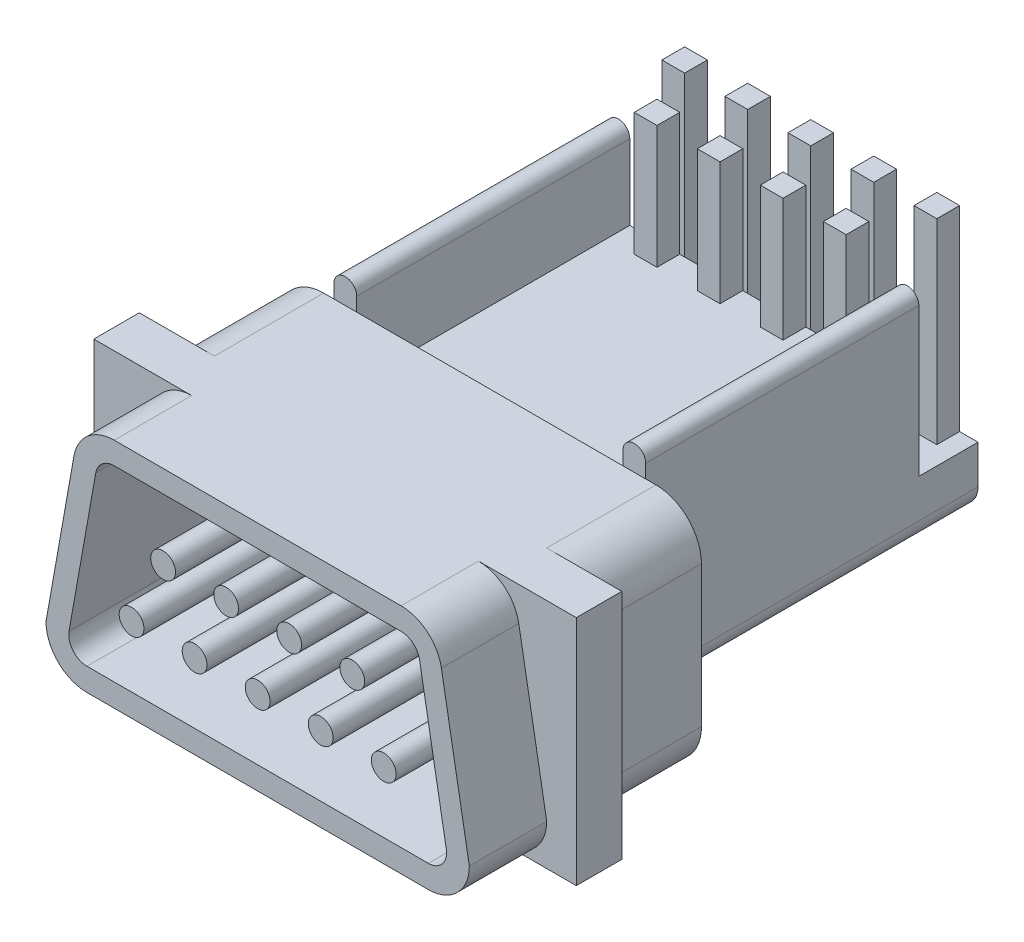
SolidWorks part; units mm, degrees
material "Калифорния"
ref_plane "Спереди" through (0, 0, 0) normal (0, 0, 1) x (1, 0, 0)
ref_plane "Сверху" through (0, 0, 0) normal (0, 1, 0) x (1, 0, 0)
ref_plane "Справа" through (0, 0, 0) normal (1, 0, 0) x (0, 0, -1)
sketch "Эскиз1" plane through (0, 0, 0) normal (0, 0, 1) x (1, 0, 0)
  line L1 (-10.6, -5.1) -> (10.6, -5.1)
  line L2 (-10.6, -5.1) -> (-10.6, 5.1)
  line L3 (-10.6, 5.1) -> (10.6, 5.1)
  line L4 (10.6, -5.1) -> (10.6, 5.1)
  line L5 (-10.6, -5.1) -> (10.6, 5.1) construction
  line L6 (-10.6, 5.1) -> (10.6, -5.1) construction
  point P0 (0, 0)
  dimension "D1" = 10.2
  dimension "D2" = 21.2
extrude "Бобышка-Вытянуть1" add sketch "Эскиз1" along normal blind 2
sketch "Эскиз2" plane through (0, 0, 2) normal (0, 0, 1) x (1, 0, 0)
  line L0 (10.6, 5.1) -> (-10.6, 5.1) construction
  line L1 (-9.3, -5.1) -> (9.3, -5.1) construction
  line L2 (-9.3, -5.1) -> (-9.3, 5.1) construction
  line L3 (-9.3, 5.1) -> (9.3, 5.1) construction
  line L4 (9.3, -5.1) -> (9.3, 5.1) construction
  line L5 (-9.3, -5.1) -> (9.3, 5.1) construction
  line L6 (-9.3, 5.1) -> (9.3, -5.1) construction
  line L7 (-6.3, 5.1) -> (6.3, 5.1)
  line L8 (-7.5, -5.1) -> (7.5, -5.1)
  line L9 (-8.0723, 3.6147) -> (-9.3, -3.3)
  line L10 (8.0723, 3.6147) -> (9.3, -3.3)
  arc A0 (-7.5, -5.1) -> (-9.3, -3.3) centre (-7.5, -3.3) cw
  arc A1 (7.5, -5.1) -> (9.3, -3.3) centre (7.5, -3.3) ccw
  arc A2 (-6.3, 5.1) -> (-8.0723, 3.6147) centre (-6.3, 3.3) ccw
  arc A3 (6.3, 5.1) -> (8.0723, 3.6147) centre (6.3, 3.3) cw
  point P0 (0, 0)
  point P10 (0, 5.1)
  point P13 (0, -5.1)
  dimension "D4" = 1.8
  dimension "D1" = 18.6
  dimension "D2" = 12.6
  dimension "D3" = 15
extrude "Бобышка-Вытянуть2" add sketch "Эскиз2" along normal blind 3.4
sketch "Эскиз3" plane through (0, 0, 0) normal (0, 0, -1) x (-1, 0, 0)
  line L0 (7.3, -5.1) -> (-7.3, -5.1)
  line L1 (10.6, -5.1) -> (-10.6, -5.1) construction
  line L2 (-9.3, -3.1) -> (-9.3, 3.1)
  line L3 (-10.6, 5.1) -> (10.6, 5.1) construction
  line L4 (-7.3, 5.1) -> (7.3, 5.1)
  line L5 (9.3, 3.1) -> (9.3, -3.1)
  line L6 (0, 0) -> (0, -10.433) construction
  arc A0 (-7.3, -5.1) -> (-9.3, -3.1) centre (-7.3, -3.1) cw
  arc A1 (-9.3, 3.1) -> (-7.3, 5.1) centre (-7.3, 3.1) cw
  arc A2 (7.3, 5.1) -> (9.3, 3.1) centre (7.3, 3.1) cw
  arc A3 (9.3, -3.1) -> (7.3, -5.1) centre (7.3, -3.1) cw
  point P17 (-6.4635, 5.1)
  point P18 (-9.3, 2.2675)
  dimension "D2" = 2
  dimension "D1" = 18.6
extrude "Бобышка-Вытянуть3" add sketch "Эскиз3" along normal blind 4.8
sketch "Эскиз4" plane through (0, 0, -4.8) normal (0, 0, -1) x (-1, 0, 0)
  line L0 (-7.3, -5.1) -> (7.3, -5.1) construction
  line L1 (6.85, -3.5) -> (-6.85, -3.5) construction
  line L2 (6.85, -3.5) -> (6.85, 6.2) construction
  line L3 (6.85, 6.2) -> (-6.85, 6.2) construction
  line L4 (-6.85, -3.5) -> (-6.85, 6.2) construction
  line L5 (6.85, -3.5) -> (-6.85, 6.2) construction
  line L6 (6.85, 6.2) -> (-6.85, -3.5) construction
  line L7 (4.85, -2.5) -> (-4.85, -2.5)
  line L8 (5.85, 5.7) -> (5.85, 2.4)
  line L9 (6.85, -2.5) -> (6.85, 5.7)
  line L10 (-5.85, 5.7) -> (-5.85, 2.4)
  line L11 (-5.85, 2.4) -> (5.85, 2.4)
  line L12 (-6.85, -2.5) -> (-6.85, 5.7)
  arc A0 (6.85, -2.5) -> (4.85, -2.5) centre (5.85, -2.5) cw
  arc A1 (-6.85, -2.5) -> (-4.85, -2.5) centre (-5.85, -2.5) ccw
  arc A2 (6.85, 5.7) -> (5.85, 5.7) centre (6.35, 5.7) ccw
  arc A3 (-6.85, 5.7) -> (-5.85, 5.7) centre (-6.35, 5.7) cw
  point P0 (0, 1.35)
  dimension "D4" = 1
  dimension "D5" = 0.5
  dimension "D7" = 0.5
  dimension "D1" = 13.7
  dimension "D2" = 9.7
  dimension "D3" = 1.6
  dimension "D6" = 3.8
extrude "Бобышка-Вытянуть4" add sketch "Эскиз4" along normal blind 12
sketch "Эскиз5" plane through (0, 0, -16.8) normal (0, 0, -1) x (-1, 0, 0)
  line L0 (6.85, -0.8) -> (-6.85, -0.8)
  line L1 (6.85, -2.5) -> (6.85, 5.7) construction
  line L2 (-6.85, 5.7) -> (-6.85, -2.5) construction
  line L3 (6.85, -0.8) -> (6.85, -2.5)
  line L4 (4.85, -2.5) -> (-4.85, -2.5)
  line L5 (-6.85, -2.5) -> (-6.85, -0.8)
  arc A0 (6.85, 5.7) -> (5.85, 5.7) centre (6.35, 5.7) ccw construction
  arc A1 (6.85, -2.5) -> (4.85, -2.5) centre (5.85, -2.5) cw
  arc A2 (-4.85, -2.5) -> (-6.85, -2.5) centre (-5.85, -2.5) cw
  dimension "D1" = 6.5
extrude "Бобышка-Вытянуть5" add sketch "Эскиз5" along normal blind 2.6
sketch "Эскиз6" plane through (0, 0, 5.4) normal (0, 0, 1) x (1, 0, 0)
  line L0 (7.5, -4.1) -> (-7.5, -4.1)
  line L1 (-8.2877, -3.1601) -> (-7.115, 3.4447)
  line L2 (-6.3, 4.1277) -> (6.3, 4.1277)
  line L3 (7.115, 3.4447) -> (8.2877, -3.1601)
  line L4 (-7.5, -5.1) -> (7.5, -5.1) construction
  line L5 (9.3, -3.3) -> (8.0723, 3.6147) construction
  line L6 (5.54, -1.42) -> (2.77, -1.42) construction
  line L7 (2.77, -1.42) -> (0, -1.42) construction
  line L8 (0, -1.42) -> (-2.77, -1.42) construction
  line L9 (-2.77, -1.42) -> (-5.54, -1.42) construction
  line L10 (4.155, 1.42) -> (1.385, 1.42) construction
  line L11 (1.385, 1.42) -> (-1.385, 1.42) construction
  line L12 (-1.385, 1.42) -> (-4.155, 1.42) construction
  line L13 (0, -1.42) -> (1.385, 1.42) construction
  line L14 (0, -1.42) -> (-1.385, 1.42) construction
  arc A0 (-7.5, -4.1) -> (-8.2877, -3.1601) centre (-7.5, -3.3) cw
  arc A1 (-7.115, 3.4447) -> (-6.3, 4.1277) centre (-6.3, 3.3) cw
  arc A2 (6.3, 4.1277) -> (7.115, 3.4447) centre (6.3, 3.3) cw
  arc A3 (8.2877, -3.1601) -> (7.5, -4.1) centre (7.5, -3.3) cw
  arc A4 (7.5, -5.1) -> (9.3, -3.3) centre (7.5, -3.3) ccw construction
  arc A5 (8.0723, 3.6147) -> (6.3, 5.1) centre (6.3, 3.3) ccw construction
  arc A6 (-6.3, 5.1) -> (-8.0723, 3.6147) centre (-6.3, 3.3) ccw construction
  arc A7 (-9.3, -3.3) -> (-7.5, -5.1) centre (-7.5, -3.3) ccw construction
  circle A8 centre (0, -1.42) radius 0.545
  circle A9 centre (-2.77, -1.42) radius 0.545
  circle A10 centre (-5.54, -1.42) radius 0.545
  circle A11 centre (2.77, -1.42) radius 0.545
  circle A12 centre (5.54, -1.42) radius 0.545
  circle A13 centre (1.385, 1.42) radius 0.545
  circle A14 centre (-1.385, 1.42) radius 0.545
  circle A15 centre (-4.155, 1.42) radius 0.545
  circle A16 centre (4.155, 1.42) radius 0.545
  dimension "D2" = 1.09
  dimension "D1" = 1
  dimension "D3" = 2.77
  dimension "D4" = 2.84
  dimension "D5" = 1.42
extrude "Вырез-Вытянуть1" cut sketch "Эскиз6" against normal blind 7
sketch "Эскиз7" plane through (0, -0.8, 0) normal (0, 1, 0) x (1, 0, 0)
  line L0 (-6.85, 19.4) -> (6.85, 19.4) construction
  line L1 (-0.5, 18.4) -> (0.5, 18.4)
  line L2 (-0.5, 18.4) -> (-0.5, 19.4)
  line L3 (-0.5, 19.4) -> (0.5, 19.4)
  line L4 (0.5, 18.4) -> (0.5, 19.4)
  line L5 (-0.5, 18.4) -> (0.5, 19.4) construction
  line L6 (-0.5, 19.4) -> (0.5, 18.4) construction
  line L8 (2.27, 18.4) -> (3.27, 18.4)
  line L9 (2.27, 18.4) -> (2.27, 19.4)
  line L10 (2.27, 19.4) -> (3.27, 19.4)
  line L11 (3.27, 18.4) -> (3.27, 19.4)
  line L12 (2.27, 18.4) -> (3.27, 19.4) construction
  line L13 (2.27, 19.4) -> (3.27, 18.4) construction
  line L14 (5.04, 18.4) -> (6.04, 18.4)
  line L15 (5.04, 18.4) -> (5.04, 19.4)
  line L16 (5.04, 19.4) -> (6.04, 19.4)
  line L17 (6.04, 18.4) -> (6.04, 19.4)
  line L18 (5.04, 18.4) -> (6.04, 19.4) construction
  line L19 (5.04, 19.4) -> (6.04, 18.4) construction
  line L20 (-3.27, 19.4) -> (-2.27, 19.4)
  line L21 (-3.27, 19.4) -> (-3.27, 18.4)
  line L22 (-3.27, 18.4) -> (-2.27, 18.4)
  line L23 (-2.27, 19.4) -> (-2.27, 18.4)
  line L24 (-3.27, 19.4) -> (-2.27, 18.4) construction
  line L25 (-3.27, 18.4) -> (-2.27, 19.4) construction
  line L26 (-6.04, 18.4) -> (-5.04, 18.4)
  line L27 (-6.04, 18.4) -> (-6.04, 19.4)
  line L28 (-6.04, 19.4) -> (-5.04, 19.4)
  line L29 (-5.04, 18.4) -> (-5.04, 19.4)
  line L30 (-6.04, 18.4) -> (-5.04, 19.4) construction
  line L31 (-6.04, 19.4) -> (-5.04, 18.4) construction
  point P0 (0, 18.9)
  point P7 (5.54, 18.9)
  point P9 (2.77, 18.9)
  point P18 (-5.54, 18.9)
  point P20 (-2.77, 18.9)
  dimension "D1" = 1
  dimension "D2" = 1
  dimension "D3" = 2.77
  dimension "D4" = 2.77
  dimension "D5" = 2.77
  dimension "D6" = 2.77
extrude "Бобышка-Вытянуть6" add sketch "Эскиз7" along normal blind 8.6
sketch "Эскиз8" plane through (0, 2.4, 0) normal (0, 1, 0) x (1, 0, 0)
  line L0 (-5.85, 16.8) -> (5.85, 16.8) construction
  line L1 (-1.885, 15.8) -> (-0.885, 15.8)
  line L2 (-1.885, 15.8) -> (-1.885, 16.8)
  line L3 (-1.885, 16.8) -> (-0.885, 16.8)
  line L4 (-0.885, 15.8) -> (-0.885, 16.8)
  line L5 (-1.885, 15.8) -> (-0.885, 16.8) construction
  line L6 (-1.885, 16.8) -> (-0.885, 15.8) construction
  line L7 (0, 15.284) -> (0, 13.164) construction
  line L8 (0.885, 15.8) -> (1.885, 15.8)
  line L9 (0.885, 15.8) -> (0.885, 16.8)
  line L10 (0.885, 16.8) -> (1.885, 16.8)
  line L11 (1.885, 15.8) -> (1.885, 16.8)
  line L12 (0.885, 15.8) -> (1.885, 16.8) construction
  line L13 (0.885, 16.8) -> (1.885, 15.8) construction
  line L14 (3.655, 15.8) -> (4.655, 15.8)
  line L15 (3.655, 15.8) -> (3.655, 16.8)
  line L16 (3.655, 16.8) -> (4.655, 16.8)
  line L17 (4.655, 15.8) -> (4.655, 16.8)
  line L18 (3.655, 15.8) -> (4.655, 16.8) construction
  line L19 (3.655, 16.8) -> (4.655, 15.8) construction
  line L20 (-4.655, 15.8) -> (-3.655, 15.8)
  line L21 (-4.655, 15.8) -> (-4.655, 16.8)
  line L22 (-4.655, 16.8) -> (-3.655, 16.8)
  line L23 (-3.655, 15.8) -> (-3.655, 16.8)
  line L24 (-4.655, 15.8) -> (-3.655, 16.8) construction
  line L25 (-4.655, 16.8) -> (-3.655, 15.8) construction
  point P0 (-1.385, 16.3)
  point P7 (1.385, 16.3)
  point P12 (4.155, 16.3)
  point P17 (-4.155, 16.3)
  dimension "D1" = 1
  dimension "D2" = 1
  dimension "D3" = 2.77
  dimension "D4" = 2.77
extrude "Бобышка-Вытянуть7" add sketch "Эскиз8" along normal up to surface (5.4 mm away) up to face at (-5.54, 7.8, -18.9)
equation "\"12ю6\"=11.573"
equation "\"D1@Эскиз5\"=6+0.5"
equation "\"D5@Эскиз6\"=1.42"
